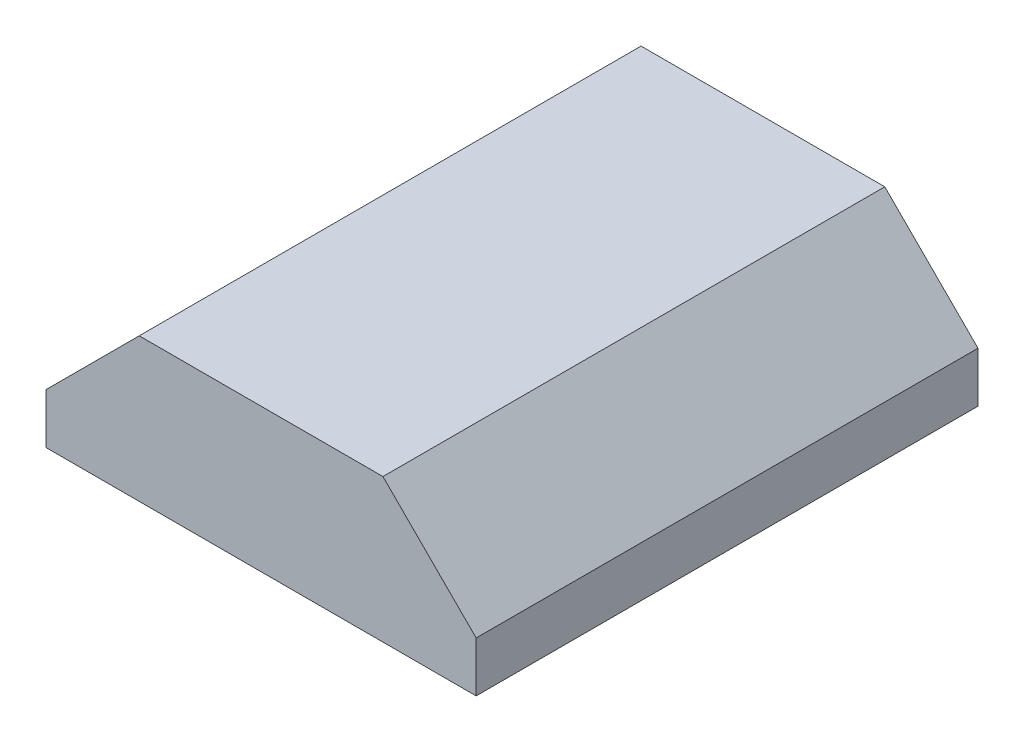
SolidWorks part; units mm, degrees
ref_plane "Ebene vorne" through (0, 0, 0) normal (0, 0, 1) x (1, 0, 0)
ref_plane "Ebene oben" through (0, 0, 0) normal (0, 1, 0) x (1, 0, 0)
ref_plane "Ebene rechts" through (0, 0, 0) normal (1, 0, 0) x (0, 0, -1)
sketch "Skizze1" plane through (0, 0, 0) normal (0, 0, 1) x (1, 0, 0)
  line L0 (0, 0) -> (0, 23680.6173) construction
  line L1 (3.4, 1.8089) -> (-3.4, 1.8089)
  line L2 (-3.4, 1.8089) -> (-6, -0.7911)
  line L3 (-6, -0.7911) -> (-6, -2.1911)
  line L4 (-6, -2.1911) -> (6, -2.1911)
  line L5 (6, -0.7911) -> (6, -2.1911)
  line L6 (3.4, 1.8089) -> (6, -0.7911)
  point P9 (0, -2.1911)
  point P11 (0, 1.8089)
  dimension "D1" = 3.4
  dimension "D2" = 6
  dimension "D3" = 4
  dimension "D4" = 135
extrude "Aufsatz-Linear austragen1" add sketch "Skizze1" along normal blind 14 contours L1 L2 L3 L4 L5 L6
